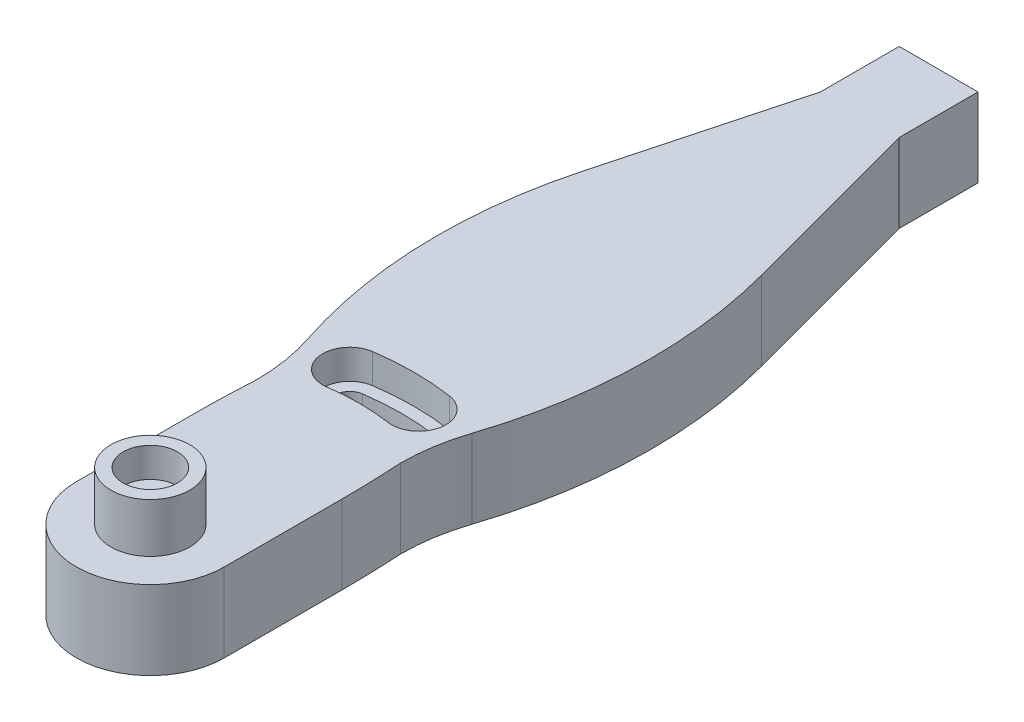
SolidWorks part; units mm, degrees
ref_plane "Front Plane" through (0, 0, 0) normal (0, 0, 1) x (1, 0, 0)
ref_plane "Top Plane" through (0, 0, 0) normal (0, 1, 0) x (1, 0, 0)
ref_plane "Right Plane" through (0, 0, 0) normal (1, 0, 0) x (0, 0, -1)
sketch "Sketch1" plane through (0, 0, 0) normal (0, 1, 0) x (1, 0, 0)
  line L0 (-7.5, 0) -> (-7.5, 11.9327)
  line L1 (7.5, 0) -> (7.5, 11.9327)
  line L3 (-4, 72) -> (4, 72) construction
  line L5 (-4, 72) -> (-4, 80)
  line L6 (-4, 80) -> (4, 80)
  line L7 (4, 80) -> (4, 72)
  line L8 (0, -1.5) -> (0, 25.5) construction
  line L9 (3.5, 23.7434) -> (3.5, 30.6301) construction
  line L10 (-3.5, 23.7434) -> (-3.5, 30.6301) construction
  line L11 (3.5, 15.8994) -> (3.5, 30.6301) construction
  line L12 (-3.5, 15.8994) -> (-3.5, 30.6301) construction
  line L13 (-1007.312, 18.0615) -> (48992.688, 18.0615) construction
  line L14 (0, 15.8994) -> (0, 30.6301) construction
  line L15 (-4, 72) -> (-9.1195, 52.8939)
  line L16 (0, -1000) -> (0, 49000) construction
  line L17 (4, 72) -> (9.1195, 52.8939)
  arc A0 (-7.5, 0) -> (7.5, 0) centre (0, 0) ccw
  arc A1 (7.5, 11.9327) -> (7.312, 18.0615) centre (-92.5, 11.9327) ccw
  arc A2 (-7.5, 11.9327) -> (-7.312, 18.0615) centre (92.5, 11.9327) cw
  circle A3 centre (0, 0) radius 1.5
  circle A4 centre (0, 0) radius 24 construction
  arc A8 (-3.5, 25.2434) -> (-3.2812, 22.2595) centre (-3.5, 23.7434) ccw
  arc A9 (3.2812, 22.2595) -> (3.5, 25.2434) centre (3.5, 23.7434) ccw
  arc A10 (3.2812, 22.2595) -> (-3.2812, 22.2595) centre (0, 0) ccw
  arc A11 (3.7188, 25.2274) -> (-3.7188, 25.2274) centre (0, 0) ccw
  arc A12 (-7.312, 18.0615) -> (-8.3152, 24.3162) centre (-27.312, 18.0615) ccw
  arc A13 (8.3152, 24.3162) -> (7.312, 18.0615) centre (27.312, 18.0615) ccw
  arc A14 (8.3152, 24.3162) -> (9.1195, 52.8939) centre (-39.1768, 39.9529) ccw
  arc A15 (-8.3152, 24.3162) -> (-9.1195, 52.8939) centre (39.1768, 39.9529) cw
  point P12 (7.5, 15)
  point P15 (-7.5, 15)
  dimension "D1" = 15
  dimension "D8" = 100
  dimension "D9" = 3
  dimension "D10" = 48
  dimension "D11" = 22.5
  dimension "D12" = 3.5
  dimension "D13" = 3.5
  dimension "D14" = 3
  dimension "D15" = 25.5
  dimension "D16" = 1.5
  dimension "D17" = 40
  dimension "D18" = 40
  dimension "D21" = 50
  dimension "D2" = 15
  dimension "D3" = 15
  dimension "D4" = 8
  dimension "D5" = 4
  dimension "D6" = 72
  dimension "D7" = 8
  dimension "D19" = 15
  dimension "D20" = 15
extrude "Boss-Extrude1" add sketch "Sketch1" along normal blind 8
sketch "Sketch2" plane through (0, 8, 0) normal (0, 1, 0) x (1, 0, 0)
  circle A0 centre (0, 0) radius 4
  circle A1 centre (0, 0) radius 1.5
  dimension "D1" = 8
extrude "Boss-Extrude2" add sketch "Sketch2" along normal blind 2
sketch "Sketch3" plane through (0, 10, 0) normal (0, 1, 0) x (1, 0, 0)
  circle A0 centre (0, 0) radius 4
  circle A1 centre (0, 0) radius 2.75
  dimension "D1" = 5.5
extrude "Boss-Extrude3" add sketch "Sketch3" along normal blind 3
sketch "Sketch4" plane through (0, 8, 0) normal (0, 1, 0) x (1, 0, 0)
  arc A0 (3.099, 21.0228) -> (3.901, 26.464) centre (3.5, 23.7434) ccw
  arc A1 (-3.901, 26.464) -> (-3.099, 21.0228) centre (-3.5, 23.7434) ccw
  arc A2 (3.099, 21.0228) -> (-3.099, 21.0228) centre (0, 0) ccw
  arc A3 (3.901, 26.464) -> (-3.901, 26.464) centre (0, 0) ccw
  dimension "D1" = 5.5
  dimension "D2" = 5.5
extrude "Cut-Extrude1" cut sketch "Sketch4" against normal blind 3
